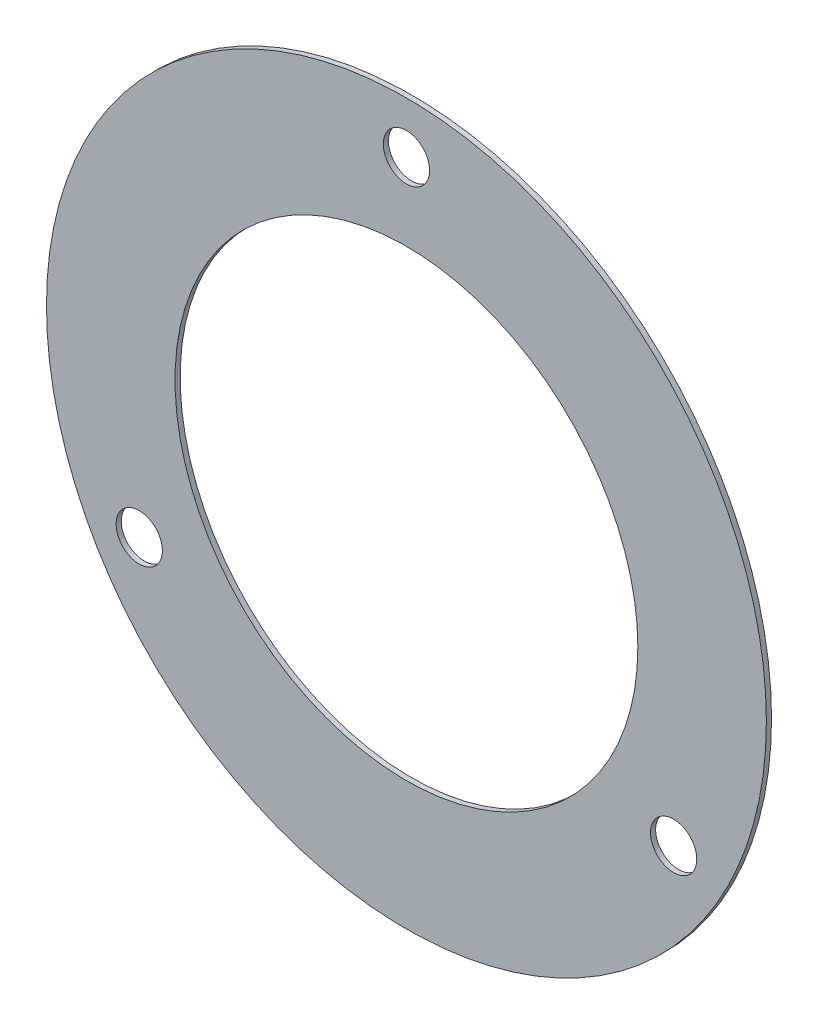
SolidWorks part; units mm, degrees
ref_plane "Piano frontale" through (0, 0, 0) normal (0, 0, 1) x (1, 0, 0)
ref_plane "Piano superiore" through (0, 0, 0) normal (0, 1, 0) x (1, 0, 0)
ref_plane "Piano destro" through (0, 0, 0) normal (1, 0, 0) x (0, 0, -1)
sketch "Schizzo1" plane through (0, 0, 0) normal (0, 0, 1) x (1, 0, 0)
  line L0 (0, 0) -> (0, 60) construction
  circle A0 centre (0, 0) radius 45
  circle A2 centre (0, 0) radius 70
  circle A3 centre (0, 60) radius 4.5
  circle A4 centre (51.9615, -30) radius 4.5
  circle A5 centre (-51.9615, -30) radius 4.5
  point P13 (0, 0)
  dimension "D1" = 90
  dimension "D2" = 60
  dimension "D3" = 140
  dimension "D4" = 9
  dimension "D5" = 3
extrude "Estrusione-Estrusione1" add sketch "Schizzo1" along normal blind 1
